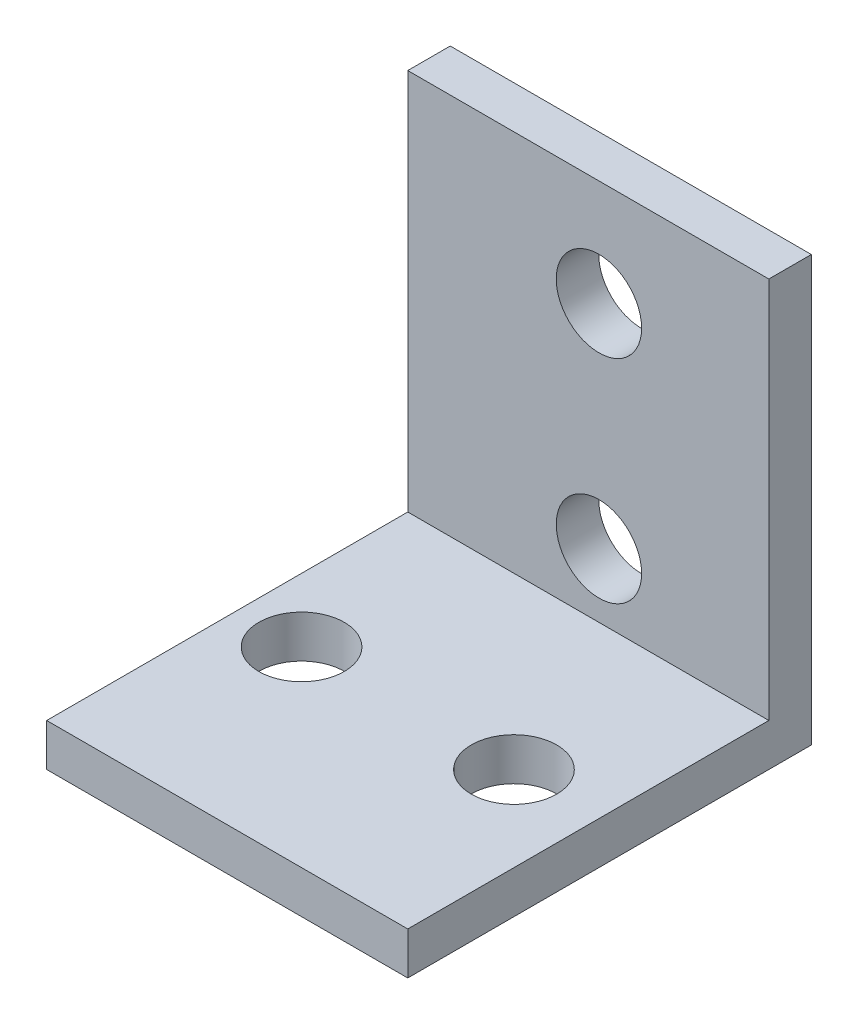
SolidWorks part; units mm, degrees
ref_plane "Front Plane" through (0, 0, 0) normal (0, 0, 1) x (1, 0, 0)
ref_plane "Top Plane" through (0, 0, 0) normal (0, 1, 0) x (1, 0, 0)
ref_plane "Right Plane" through (0, 0, 0) normal (1, 0, 0) x (0, 0, -1)
sketch "Sketch1" plane through (0, 0, 0) normal (0, 0, 1) x (1, 0, 0)
  line L1 (0, 0) -> (21.59, 0)
  line L2 (0, 0) -> (0, 25.4)
  line L3 (0, 25.4) -> (21.59, 25.4)
  line L4 (21.59, 0) -> (21.59, 25.4)
  dimension "D1" = 21.59
  dimension "D2" = 25.4
extrude "Boss-Extrude1" add sketch "Sketch1" along normal blind 24.13
sketch "Sketch2" plane through (21.59, 0, 0) normal (1, 0, 0) x (0, 0, -1)
  line L0 (-24.13, 25.4) -> (0, 25.4) construction
  line L1 (-2.54, 25.4) -> (-24.13, 25.4)
  line L2 (-2.54, 25.4) -> (-2.54, 2.54)
  line L3 (-2.54, 2.54) -> (-24.13, 2.54)
  line L4 (-24.13, 25.4) -> (-24.13, 2.54)
  line L5 (-24.13, 0) -> (-24.13, 25.4) construction
  dimension "D1" = 21.59
  dimension "D2" = 22.86
extrude "Cut-Extrude1" cut sketch "Sketch2" against normal through all
sketch "Sketch3" plane through (0, 0, 2.54) normal (0, 0, 1) x (1, 0, 0)
  line L0 (0, 25.4) -> (21.59, 25.4) construction
  line L1 (21.59, 2.54) -> (21.59, 25.4) construction
  circle A0 centre (11.43, 19.05) radius 2.5527
  circle A1 centre (11.43, 6.35) radius 2.5527
  dimension "D1" = 5.1054
  dimension "D2" = 5.1054
  dimension "D3" = 6.35
  dimension "D4" = 12.7
  dimension "D5" = 10.16
  dimension "D6" = 10.16
extrude "Cut-Extrude2" cut sketch "Sketch3" against normal through all
sketch "Sketch4" plane through (0, 2.54, 0) normal (0, 1, 0) x (1, 0, 0)
  line L0 (21.59, -24.13) -> (21.59, -2.54) construction
  line L1 (0, -24.13) -> (21.59, -24.13) construction
  circle A0 centre (16.51, -12.7) radius 2.5527
  circle A1 centre (3.81, -12.7) radius 2.5527
  dimension "D1" = 5.1054
  dimension "D2" = 5.1054
  dimension "D3" = 5.08
  dimension "D4" = 11.43
  dimension "D5" = 11.43
  dimension "D6" = 12.7
extrude "Cut-Extrude3" cut sketch "Sketch4" against normal through all
